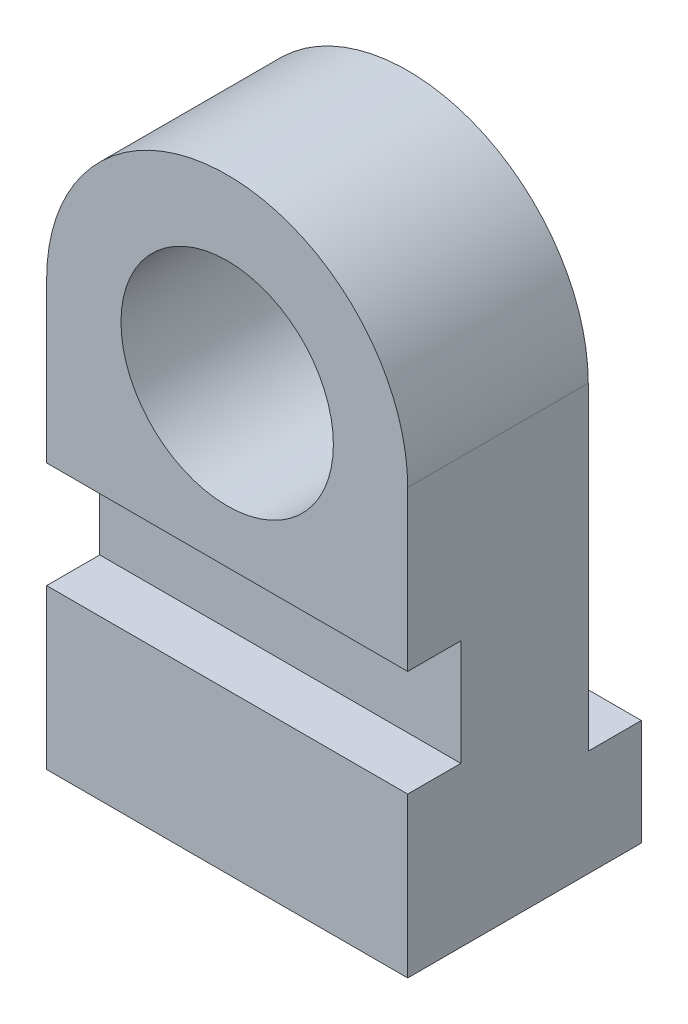
SolidWorks part; units mm, degrees
ref_plane "Front Plane" through (0, 0, 0) normal (0, 0, 1) x (1, 0, 0)
ref_plane "Top Plane" through (0, 0, 0) normal (0, 1, 0) x (1, 0, 0)
ref_plane "Right Plane" through (0, 0, 0) normal (1, 0, 0) x (0, 0, -1)
sketch "Sketch1" plane through (0, 0, 0) normal (0, 0, 1) x (1, 0, 0)
  line L0 (0, 0) -> (-49465.7534, 0) construction
  line L1 (-49465.7534, 0) -> (-15465.7534, 0) construction
  line L2 (-49465.7534, 40000) -> (-15465.7534, 40000) construction
  line L3 (-32465.7534, 58082.1918) -> (-32465.7534, 0) construction
  line L4 (-49465.7534, 40000) -> (-49465.7534, 0)
  line L5 (-49465.7534, 0) -> (-15465.7534, 0)
  line L6 (-15465.7534, 0) -> (-15465.7534, 40000)
  arc A0 (-49465.7534, 40000) -> (-15465.7534, 40000) centre (-32465.7534, 40000) cw
  circle A1 centre (-32465.7534, 40000) radius 10000
  dimension "D2" = 17000
  dimension "D3" = 20000
  dimension "D1" = 40000
extrude "Boss-Extrude1" add sketch "Sketch1" along normal blind 17000
sketch "Sketch2" plane through (0, 0, 17000) normal (0, 0, 1) x (1, 0, 0)
  line L0 (-49465.7534, 40000) -> (-49465.7534, 0) construction
  line L1 (-49465.7534, 25000) -> (-15465.7534, 25000)
  line L2 (-49465.7534, 25000) -> (-49465.7534, 15000)
  line L3 (-49465.7534, 15000) -> (-15465.7534, 15000)
  line L4 (-15465.7534, 25000) -> (-15465.7534, 15000)
  line L5 (-15465.7534, 0) -> (-15465.7534, 40000) construction
  dimension "D1" = 15000
  dimension "D2" = 10000
extrude "Cut-Extrude1" cut sketch "Sketch2" against normal blind 5000
sketch "Sketch3" plane through (0, 0, 0) normal (0, 0, -1) x (-1, 0, 0)
  line L0 (15465.7534, 0) -> (15465.7534, 40000) construction
  line L1 (15465.7534, 0) -> (49465.7534, 0)
  line L2 (15465.7534, 0) -> (15465.7534, 10000)
  line L3 (15465.7534, 10000) -> (49465.7534, 10000)
  line L4 (49465.7534, 0) -> (49465.7534, 10000)
  line L5 (49465.7534, 40000) -> (49465.7534, 0) construction
  dimension "D1" = 10000
extrude "Boss-Extrude2" add sketch "Sketch3" along normal blind 5000
